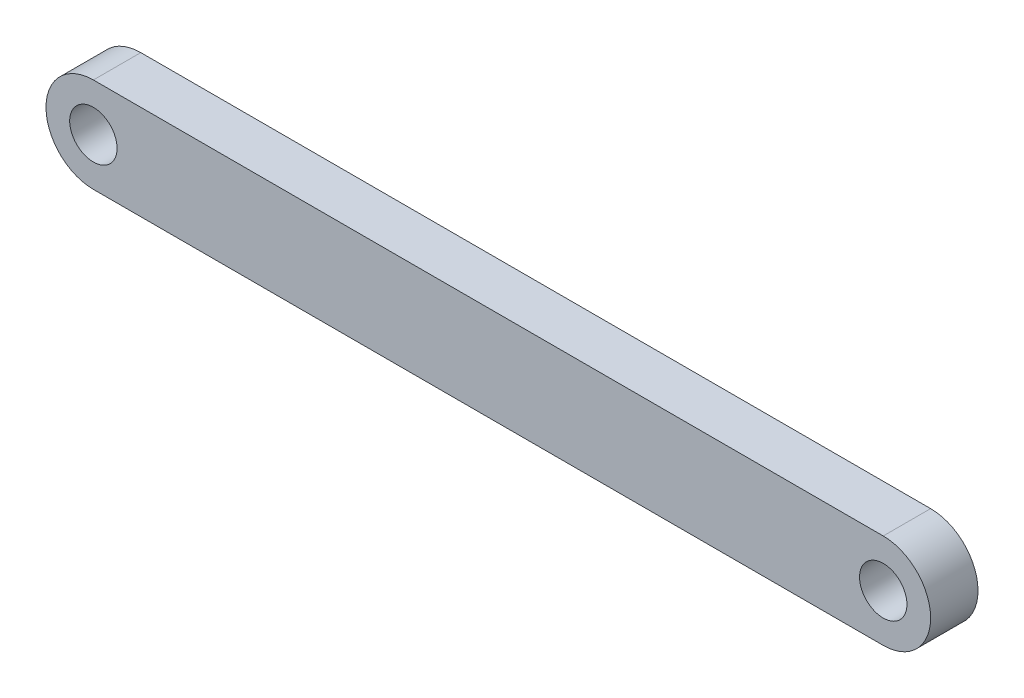
SolidWorks part; units mm, degrees
ref_plane "Front Plane" through (0, 0, 0) normal (0, 0, 1) x (1, 0, 0)
ref_plane "Top Plane" through (0, 0, 0) normal (0, 1, 0) x (1, 0, 0)
ref_plane "Right Plane" through (0, 0, 0) normal (1, 0, 0) x (0, 0, -1)
sketch "Sketch1" plane through (0, 0, 0) normal (0, 0, 1) x (1, 0, 0)
  line L0 (0, 0) -> (-50, 0)
  dimension "D1" = 50
sketch "Sketch2" plane through (0, 0, 0) normal (0, 0, 1) x (1, 0, 0)
  line L0 (-50, 3) -> (0, 3)
  line L1 (-50, -3) -> (0, -3)
  circle A0 centre (-50, 0) radius 1.5
  circle A1 centre (0, 0) radius 1.5
  arc A2 (-50, 3) -> (-50, -3) centre (-50, 0) ccw
  arc A3 (0, -3) -> (0, 3) centre (0, 0) ccw
  dimension "D1" = 3
  dimension "D2" = 6
  dimension "D3" = 3
  dimension "D4" = 6
extrude "Boss-Extrude1" add sketch "Sketch2" along normal blind 3
